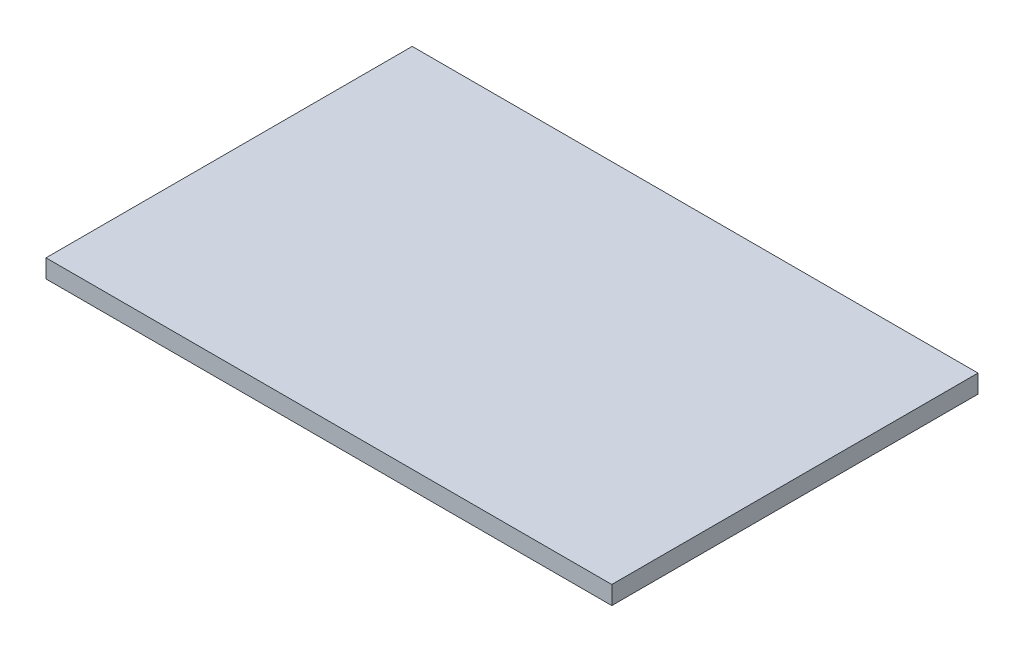
SolidWorks part; units mm, degrees
ref_plane "Front Plane" through (0, 0, 0) normal (0, 0, 1) x (1, 0, 0)
ref_plane "Top Plane" through (0, 0, 0) normal (0, 1, 0) x (1, 0, 0)
ref_plane "Right Plane" through (0, 0, 0) normal (1, 0, 0) x (0, 0, -1)
sketch "Sketch1" plane through (0, 0, 0) normal (0, 1, 0) x (1, 0, 0)
  line L1 (0, 0) -> (309, 0)
  line L2 (0, 0) -> (0, 200)
  line L3 (0, 200) -> (309, 200)
  line L4 (309, 0) -> (309, 200)
  dimension "D1" = 309
  dimension "D2" = 200
extrude "Boss-Extrude1" add sketch "Sketch1" along normal blind 10
